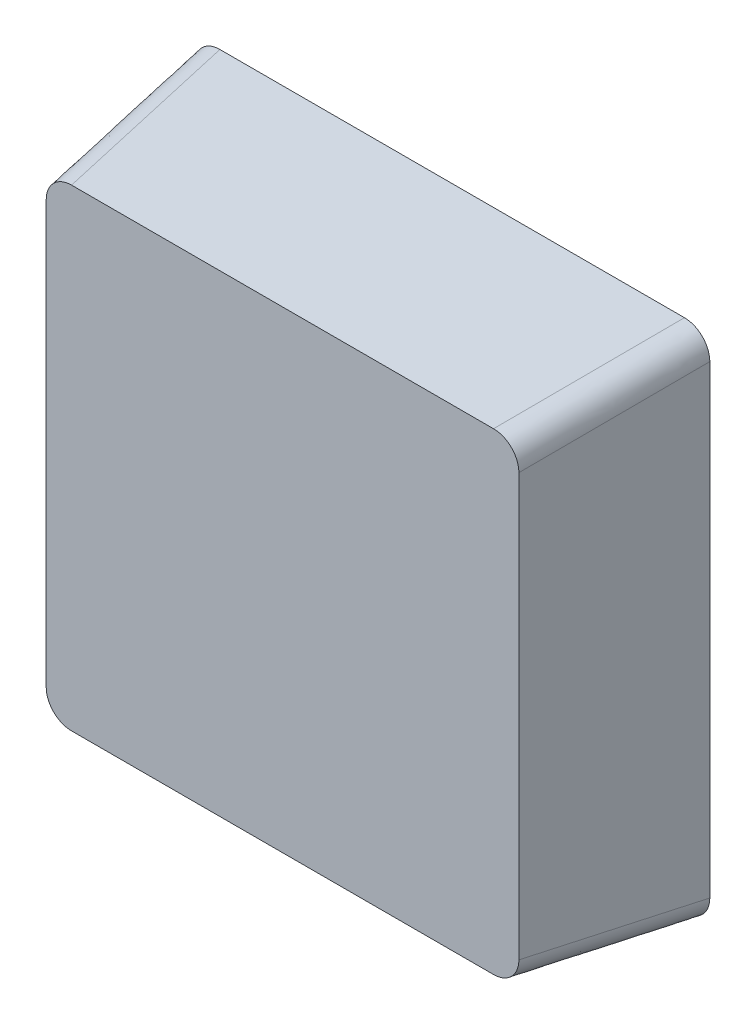
SolidWorks part; units mm, degrees
ref_plane "Plan de face" through (0, 0, 0) normal (0, 0, 1) x (1, 0, 0)
ref_plane "Plan de dessus" through (0, 0, 0) normal (0, 1, 0) x (1, 0, 0)
ref_plane "Plan de droite" through (0, 0, 0) normal (1, 0, 0) x (0, 0, -1)
sketch "Esquisse1" plane through (0, 0, 0) normal (0, 0, 1) x (1, 0, 0)
  line L1 (-27.75, 27.75) -> (27.75, 27.75)
  line L2 (-27.75, 27.75) -> (-27.75, -27.75)
  line L3 (-27.75, -27.75) -> (27.75, -27.75)
  line L4 (27.75, 27.75) -> (27.75, -27.75)
  line L5 (-27.75, 27.75) -> (27.75, -27.75) construction
  line L6 (-27.75, -27.75) -> (27.75, 27.75) construction
  point P0 (0, 0)
  dimension "D1" = 55.5
  dimension "D2" = 55.5
ref_plane "Plan1" through (0, 0, -20) normal (0, 0, 1) x (1, 0, 0)
sketch "Esquisse2" plane through (0, 0, -20) normal (0, 0, 1) x (1, 0, 0)
  line L0 (-27.75, -27.75) -> (27.75, -27.75) construction
  line L1 (-30.3323, 30.25) -> (30.1677, 30.25)
  line L2 (-30.3323, 30.25) -> (-30.3335, -30.25)
  line L3 (-30.3335, -30.25) -> (30.1665, -30.25)
  line L4 (30.1677, 30.25) -> (30.1665, -30.25)
  line L5 (-30.3323, 30.25) -> (30.1665, -30.25) construction
  line L6 (-30.3335, -30.25) -> (30.1677, 30.25) construction
  dimension "D1" = 60.5
  dimension "D2" = 60.5
  dimension "D3" = 60.5
  dimension "D4" = 60.5
  dimension "D5" = 2.5
loft "Lissage1" add profiles "Esquisse1", "Esquisse2"
ref_plane "Plan2" through (0, 0, -20) normal (0, 0, 1) x (1, 0, 0)
sketch "Esquisse3" plane through (0, 0, -20) normal (0, 0, 1) x (1, 0, 0)
  line L5 (-22, -9.65) -> (22, -9.65)
  line L6 (-22, -9.65) -> (-22, -3.65)
  line L10 (-22, -3.65) -> (22, -3.65)
  line L11 (22, -9.65) -> (22, -3.65)
  line L12 (-30.3335, -30.25) -> (30.1665, -30.25) construction
  line L13 (27.75, -27.75) -> (27.75, 27.75) construction
  line L14 (-22, -22.95) -> (22, -22.95)
  line L15 (-22, -22.95) -> (-22, -16.95)
  line L16 (-22, -16.95) -> (22, -16.95)
  line L17 (22, -22.95) -> (22, -16.95)
  line L18 (-22, -22.95) -> (22, -16.95) construction
  line L19 (-22, -16.95) -> (22, -22.95) construction
  line L20 (-22, -9.65) -> (22, -3.65) construction
  line L21 (-22, -3.65) -> (22, -9.65) construction
  line L22 (-22, 3.65) -> (22, 3.65)
  line L23 (-22, 3.65) -> (-22, 9.65)
  line L24 (-22, 9.65) -> (22, 9.65)
  line L25 (22, 3.65) -> (22, 9.65)
  line L26 (-22, 3.65) -> (22, 9.65) construction
  line L27 (-22, 9.65) -> (22, 3.65) construction
  line L28 (-22, 16.95) -> (22, 16.95)
  line L29 (-22, 16.95) -> (-22, 22.95)
  line L30 (-22, 22.95) -> (22, 22.95)
  line L31 (22, 16.95) -> (22, 22.95)
  line L32 (-22, 16.95) -> (22, 22.95) construction
  line L33 (-22, 22.95) -> (22, 16.95) construction
  point P1 (0, -6.65)
  point P6 (0, 6.65)
  point P11 (0, 19.95)
  point P12 (0, -19.95)
  dimension "D1" = 44
  dimension "D2" = 44
  dimension "D3" = 44
  dimension "D4" = 7.3
  dimension "D5" = 6
  dimension "D6" = 7.3
  dimension "D7" = 44
  dimension "D8" = 5.75
  dimension "D9" = 7.3
  dimension "D10" = 7.3
  dimension "D11" = 6
  dimension "D12" = 6
  dimension "D13" = 6
extrude "Enlèv. mat.-Extru.3" cut sketch "Esquisse3" along normal blind 15 draft 1
fillet "Congé1" radius 3 4 edges
